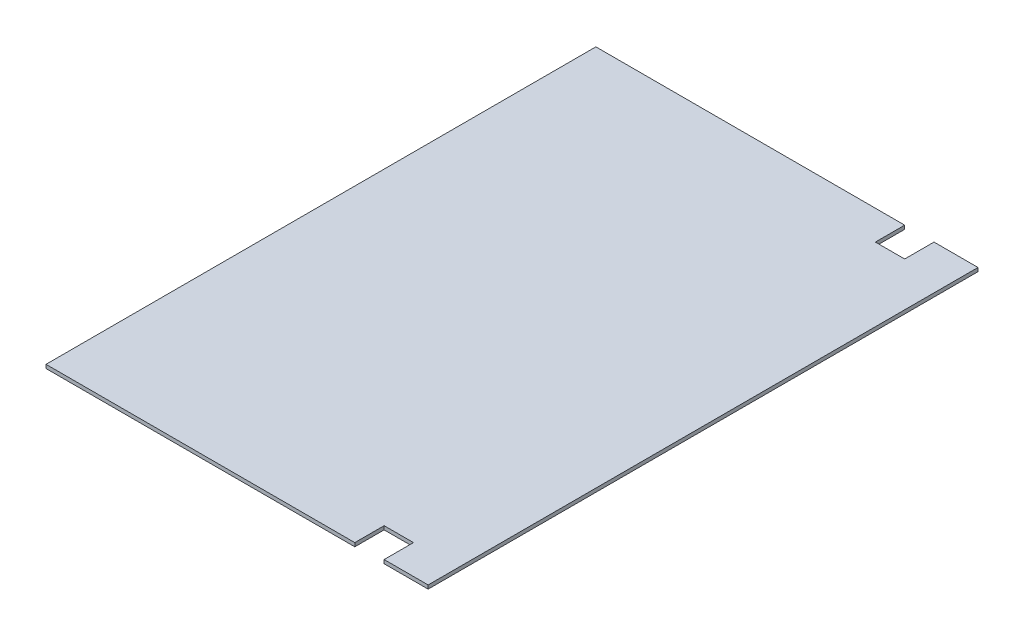
SolidWorks part; units mm, degrees
material "Glass"
ref_plane "Front Plane" through (0, 0, 0) normal (0, 0, 1) x (1, 0, 0)
ref_plane "Top Plane" through (0, 0, 0) normal (0, 1, 0) x (1, 0, 0)
ref_plane "Right Plane" through (0, 0, 0) normal (1, 0, 0) x (0, 0, -1)
sketch "Sketch1" plane through (0, 0, 0) normal (0, 1, 0) x (1, 0, 0)
  line L0 (0, 0) -> (330.962, 0)
  line L2 (0, 0) -> (0, 476.25)
  line L3 (0, 476.25) -> (330.962, 476.25)
  line L4 (330.962, 0) -> (330.962, 476.25)
  dimension "D1" = 476.25
  dimension "D2" = 330.962
extrude "Boss-Extrude1" add sketch "Sketch1" along normal blind 3.175 contours L3 L4 L0 L2
sketch "Sketch2" plane through (0, 3.175, 0) normal (0, 1, 0) x (1, 0, 0)
  line L0 (0, 0) -> (330.962, 0) construction
  line L1 (267.462, 0) -> (292.862, 0)
  line L2 (267.462, 0) -> (267.462, 25.4)
  line L3 (267.462, 25.4) -> (292.862, 25.4)
  line L4 (292.862, 0) -> (292.862, 25.4)
  line L5 (0, 0) -> (0, 476.25) construction
  line L6 (0, 476.25) -> (330.962, 476.25) construction
  line L7 (292.862, 476.25) -> (267.462, 476.25)
  line L8 (292.862, 476.25) -> (292.862, 450.85)
  line L9 (292.862, 450.85) -> (267.462, 450.85)
  line L10 (267.462, 476.25) -> (267.462, 450.85)
  dimension "D1" = 25.4
  dimension "D2" = 25.4
  dimension "D3" = 267.462
  dimension "D4" = 25.4
  dimension "D5" = 25.4
extrude "Cut-Extrude1" cut sketch "Sketch2" against normal through all
